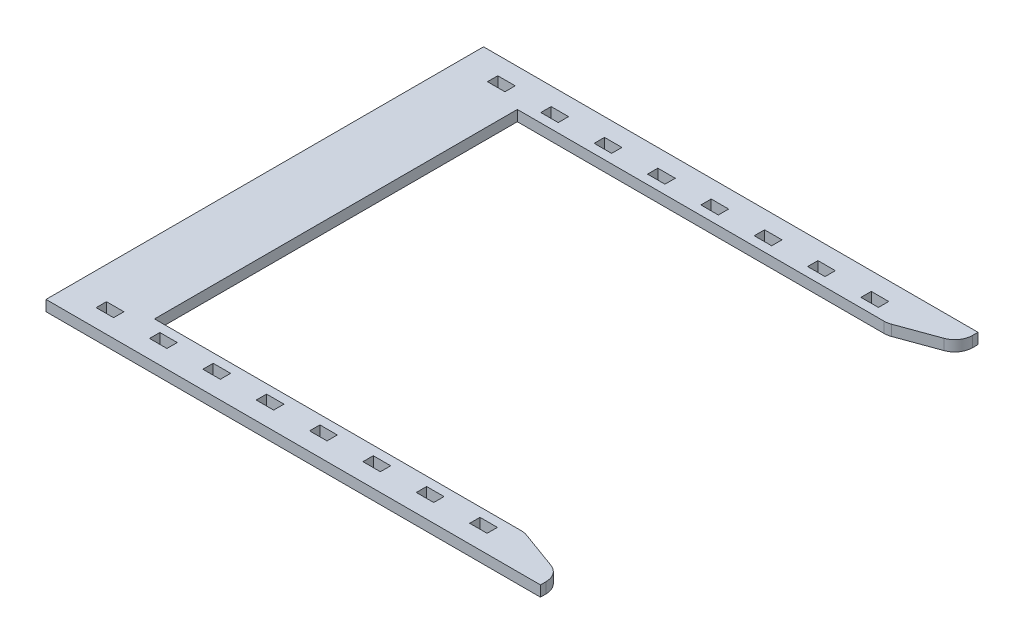
SolidWorks part; units mm, degrees
ref_plane "Front Plane" through (0, 0, 0) normal (0, 0, 1) x (1, 0, 0)
ref_plane "Top Plane" through (0, 0, 0) normal (0, 1, 0) x (1, 0, 0)
ref_plane "Right Plane" through (0, 0, 0) normal (1, 0, 0) x (0, 0, -1)
sketch "Sketch1" plane through (0, 0, 0) normal (0, 1, 0) x (1, 0, 0)
  line L1 (-150, -118) -> (150, -118)
  line L2 (-150, -118) -> (-150, 118)
  line L3 (-150, 118) -> (150, 118)
  line L4 (150, -118) -> (150, 118)
  line L5 (-150, -118) -> (150, 118) construction
  line L6 (-150, 118) -> (150, -118) construction
  line L7 (150, -102) -> (-98, -102)
  line L8 (150, -102) -> (150, 102)
  line L9 (150, 102) -> (-98, 102)
  line L10 (-98, -102) -> (-98, 102)
  line L11 (150, -102) -> (-98, 102) construction
  line L12 (150, 102) -> (-98, -102) construction
  point P0 (0, 0)
  point P10 (26, 0)
  point P11 (-98, 0)
  dimension "D1" = 300
  dimension "D2" = 236
  dimension "D3" = 204
  dimension "D4" = 248
extrude "Boss-Extrude1" add sketch "Sketch1" along normal blind 6 contours L7 L10 L9 L4 L3 L2 L1
sketch "Sketch2" plane through (0, 6, 0) normal (0, 1, 0) x (1, 0, 0)
  line L0 (150, -110) -> (115, -110) construction
  line L1 (150, -118) -> (150, -102) construction
  line L2 (80.1, -112.9) -> (80.1, -107.1)
  line L3 (110.1, -112.9) -> (119.9, -112.9)
  line L4 (110.1, -112.9) -> (110.1, -107.1)
  line L5 (110.1, -107.1) -> (119.9, -107.1)
  line L6 (119.9, -112.9) -> (119.9, -107.1)
  line L7 (110.1, -112.9) -> (119.9, -107.1) construction
  line L8 (110.1, -107.1) -> (119.9, -112.9) construction
  line L9 (80.1, -107.1) -> (89.9, -107.1)
  line L10 (80.1, -112.9) -> (89.9, -112.9)
  line L11 (89.9, -112.9) -> (89.9, -107.1)
  line L12 (50.1, -112.9) -> (50.1, -107.1)
  line L13 (50.1, -107.1) -> (59.9, -107.1)
  line L14 (50.1, -112.9) -> (59.9, -112.9)
  line L15 (59.9, -112.9) -> (59.9, -107.1)
  line L16 (20.1, -112.9) -> (20.1, -107.1)
  line L17 (20.1, -107.1) -> (29.9, -107.1)
  line L18 (20.1, -112.9) -> (29.9, -112.9)
  line L19 (29.9, -112.9) -> (29.9, -107.1)
  line L20 (-9.9, -112.9) -> (-9.9, -107.1)
  line L21 (-9.9, -107.1) -> (-0.1, -107.1)
  line L22 (-9.9, -112.9) -> (-0.1, -112.9)
  line L23 (-0.1, -112.9) -> (-0.1, -107.1)
  line L24 (-39.9, -112.9) -> (-39.9, -107.1)
  line L25 (-39.9, -107.1) -> (-30.1, -107.1)
  line L26 (-39.9, -112.9) -> (-30.1, -112.9)
  line L27 (-30.1, -112.9) -> (-30.1, -107.1)
  line L28 (-69.9, -112.9) -> (-69.9, -107.1)
  line L29 (-69.9, -107.1) -> (-60.1, -107.1)
  line L30 (-69.9, -112.9) -> (-60.1, -112.9)
  line L31 (-60.1, -112.9) -> (-60.1, -107.1)
  line L32 (-99.9, -112.9) -> (-99.9, -107.1)
  line L33 (-99.9, -107.1) -> (-90.1, -107.1)
  line L34 (-99.9, -112.9) -> (-90.1, -112.9)
  line L35 (-90.1, -112.9) -> (-90.1, -107.1)
  line L40 (-129.9, -112.9) -> (-129.9, -107.1) [skipped]
  line L41 (-129.9, -107.1) -> (-120.1, -107.1) [skipped]
  line L42 (-129.9, -112.9) -> (-120.1, -112.9) [skipped]
  line L43 (-120.1, -112.9) -> (-120.1, -107.1) [skipped]
  dimension "D1" = 35
  dimension "D2" = 9.8
  dimension "D3" = 5.8
  dimension "D4" = 9
extrude "Cut-Extrude1" cut sketch "Sketch2" against normal blind 6
mirror "Mirror1" about plane through (0, 0, 0) normal (0, 0, 1) of "Cut-Extrude1"
sketch "Sketch5" plane through (0, 6, 0) normal (0, 1, 0) x (1, 0, 0)
  line L0 (-150, -118) -> (150, -118) construction
  line L1 (150, 118) -> (130, 118)
  line L2 (150, 118) -> (150, -118)
  line L3 (150, -118) -> (130, -118)
  line L4 (130, 118) -> (130, -118)
  line L5 (150, 118) -> (130, -118) construction
  line L6 (150, -118) -> (130, 118) construction
  point P4 (140, 0)
  dimension "D1" = 20
extrude "Cut-Extrude2" cut sketch "Sketch5" against normal blind 6
sketch "Sketch6" plane through (0, 6, 0) normal (0, 1, 0) x (1, 0, 0)
  line L1 (-98, 102) -> (-108, 102)
  line L2 (-98, 102) -> (-98, -102)
  line L3 (-98, -102) -> (-108, -102)
  line L4 (-108, 102) -> (-108, -102)
  line L5 (-98, 102) -> (-108, -102) construction
  line L6 (-98, -102) -> (-108, 102) construction
  point P4 (-103, 0)
  dimension "D1" = 10
extrude "Cut-Extrude3" cut sketch "Sketch6" against normal blind 20
sketch "Sketch7" plane through (0, 6, 0) normal (0, 1, 0) x (1, 0, 0)
  line L0 (-150, -118) -> (130, -118) construction
  line L1 (-150, 118) -> (-118, 118)
  line L2 (-150, 118) -> (-150, -118)
  line L3 (-150, -118) -> (-118, -118)
  line L4 (-118, 118) -> (-118, -118)
  line L5 (-150, 118) -> (-118, -118) construction
  line L6 (-150, -118) -> (-118, 118) construction
  line L7 (-108, 102) -> (-108, -102) construction
  point P4 (-134, 0)
  dimension "D1" = 10
extrude "Cut-Extrude4" cut sketch "Sketch7" against normal blind 20
sketch "Sketch8" plane through (0, 0, 118) normal (0, 0, 1) x (1, 0, 0)
  line L4 (130, 6) -> (-118, 6)
  line L5 (-118, 6) -> (-118, 0)
  line L6 (-118, 0) -> (130, 0)
  line L7 (130, 0) -> (130, 6)
  line L8 (130, 6) -> (-118, 6)
  line L9 (-118, 6) -> (-118, 0)
  line L10 (-118, 0) -> (130, 0)
  line L11 (130, 0) -> (130, 6)
  dimension "D1" = 0
extrude "Boss-Extrude2" add sketch "Sketch8" along normal blind 5
mirror "Mirror2" about plane through (0, 0, 0) normal (0, 0, 1) of "Boss-Extrude2"
sketch "Sketch10" plane through (0, 6, 0) normal (0, 1, 0) x (1, 0, 0)
  line L0 (130, -102) -> (-108, -102) construction
  line L1 (-108, 102) -> (-78, 102)
  line L2 (-108, 102) -> (-108, -102)
  line L3 (-108, -102) -> (-78, -102)
  line L4 (-78, 102) -> (-78, -102)
  line L5 (-108, 102) -> (-78, -102) construction
  line L6 (-108, -102) -> (-78, 102) construction
  point P4 (-93, 0)
  dimension "D1" = 30
extrude "Boss-Extrude3" add sketch "Sketch10" against normal through all
sketch "Sketch11" plane through (130, 0, 0) normal (1, 0, 0) x (0, 0, -1)
  line L0 (-102, 6) -> (-123, 6) construction
  line L1 (-123, 6) -> (-123, 0) construction
  line L2 (-123, 0) -> (-102, 0) construction
  line L3 (-102, 0) -> (-102, 6) construction
  line L4 (102, 6) -> (102, 0) construction
  line L5 (102, 0) -> (123, 0) construction
  line L6 (123, 0) -> (123, 6) construction
  line L7 (123, 6) -> (102, 6) construction
  line L8 (-102, 6) -> (-123, 6)
  line L9 (-123, 6) -> (-123, 0)
  line L10 (-123, 0) -> (-102, 0)
  line L11 (-102, 0) -> (-102, 6)
  line L12 (102, 6) -> (102, 0)
  line L13 (102, 0) -> (123, 0)
  line L14 (123, 0) -> (123, 6)
  line L15 (123, 6) -> (102, 6)
extrude "Boss-Extrude4" add sketch "Sketch11" along normal blind 30
chamfer "Chamfer1" distance 30 angle 20 2 edges at (160, 3, 102) (160, 3, -102)
fillet "Fillet1" radius 10 4 edges at (160, 3, 112.9191) (130, 3, 102) (130, 3, -102) (160, 3, -112.9191)
